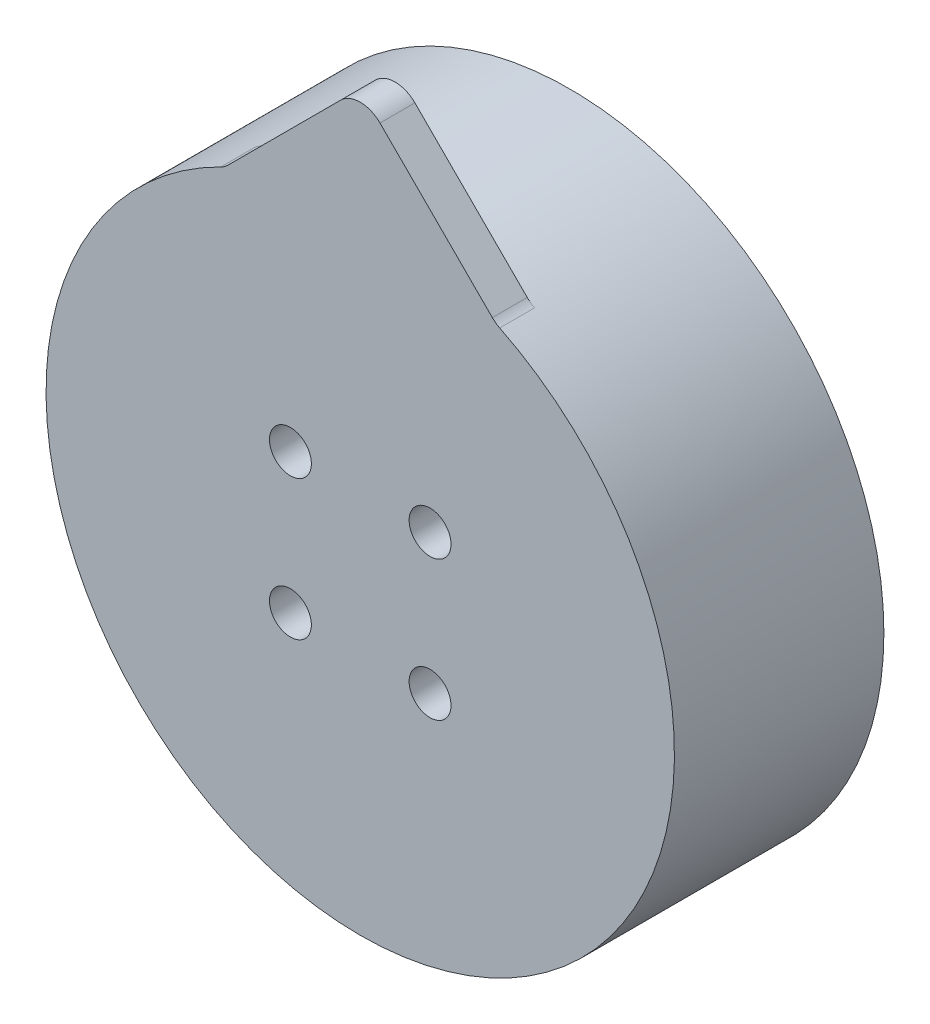
SolidWorks part; units mm, degrees
ref_plane "Front Plane" through (0, 0, 0) normal (0, 0, 1) x (1, 0, 0)
ref_plane "Top Plane" through (0, 0, 0) normal (0, 1, 0) x (1, 0, 0)
ref_plane "Right Plane" through (0, 0, 0) normal (1, 0, 0) x (0, 0, -1)
sketch "Sketch1" plane through (0, 0, 0) normal (0, 0, 1) x (1, 0, 0)
  circle A1 centre (0, 0) radius 21.844
  circle A2 centre (0, 0) radius 28.575
  dimension "D1" = 43.688
  dimension "D2" = 57.15
extrude "Boss-Extrude1" add sketch "Sketch1" along normal blind 12.7
sketch "Sketch2" plane through (0, 0, 12.7) normal (0, 0, 1) x (1, 0, 0)
  circle A1 centre (0, 0) radius 28.575
  circle A2 centre (0, 0) radius 28.575
  dimension "D1" = 0
extrude "Boss-Extrude2" add sketch "Sketch2" along normal blind 6.35
sketch "Sketch3" plane through (0, 0, 19.05) normal (0, 0, 1) x (1, 0, 0)
  line L0 (-12.3148, 25.7852) -> (0, 38.1)
  line L1 (0, 38.1) -> (12.3148, 25.7852)
  circle A0 centre (0, 0) radius 28.575 construction
  circle A2 centre (0, 0) radius 28.575
  arc A3 (12.3148, 25.7852) -> (-12.3148, 25.7852) centre (0, 0) ccw
  dimension "D1" = 38.1
  dimension "D2" = 0
extrude "Boss-Extrude3" add sketch "Sketch3" against normal blind 3.175
fillet "Fillet1" radius 2.54 3 edges at (0, 38.1, 17.4625) (12.3148, 25.7852, 17.4625) (-12.3148, 25.7852, 17.4625)
sketch "Sketch4" plane through (0, 0, 0) normal (0, 0, -1) x (-1, 0, 0)
  line L0 (0, 21.844) -> (0, -21.844) construction
  line L1 (-21.844, 0) -> (21.844, 0) construction
  line L2 (-15.446, -15.446) -> (15.446, 15.446) construction
  line L3 (-15.446, 15.446) -> (15.446, -15.446) construction
  circle A0 centre (0, 0) radius 21.844 construction
  circle A1 centre (0, 0) radius 21.844 construction
  circle A2 centre (0, 21.844) radius 1.5875
  circle A3 centre (15.446, 15.446) radius 1.5875
  circle A4 centre (21.844, 0) radius 1.5875
  circle A5 centre (15.446, -15.446) radius 1.5875
  circle A6 centre (0, -21.844) radius 1.5875
  circle A7 centre (-15.446, -15.446) radius 1.5875
  circle A8 centre (-21.844, 0) radius 1.5875
  circle A9 centre (-15.446, 15.446) radius 1.5875
  dimension "D3" = 3.175
  dimension "D1" = 90
  dimension "D2" = 45
extrude "Cut-Extrude1" cut sketch "Sketch4" against normal up to surface (12.7 mm away) up to face at (21.844, 0, 12.7)
sketch "Sketch5" plane through (0, 0, 12.7) normal (0, 0, -1) x (-1, 0, 0)
  line L1 (-6.35, -6.35) -> (6.35, -6.35) construction
  line L2 (-6.35, -6.35) -> (-6.35, 6.35) construction
  line L3 (-6.35, 6.35) -> (6.35, 6.35) construction
  line L4 (6.35, -6.35) -> (6.35, 6.35) construction
  line L5 (-6.35, -6.35) -> (6.35, 6.35) construction
  line L6 (-6.35, 6.35) -> (6.35, -6.35) construction
  circle A0 centre (-6.35, 6.35) radius 3.175
  circle A1 centre (6.35, 6.35) radius 3.175
  circle A2 centre (6.35, -6.35) radius 3.175
  circle A3 centre (-6.35, -6.35) radius 3.175
  point P0 (0, 0)
  dimension "D2" = 6.35
  dimension "D1" = 12.7
extrude "Cut-Extrude2" cut sketch "Sketch5" against normal blind 3.175
sketch "Sketch6" plane through (0, 0, 15.875) normal (0, 0, -1) x (-1, 0, 0)
  line L1 (-6.35, -6.35) -> (6.35, -6.35) construction
  line L2 (-6.35, -6.35) -> (-6.35, 6.35) construction
  line L3 (-6.35, 6.35) -> (6.35, 6.35) construction
  line L4 (6.35, -6.35) -> (6.35, 6.35) construction
  line L5 (-6.35, -6.35) -> (6.35, 6.35) construction
  line L6 (-6.35, 6.35) -> (6.35, -6.35) construction
  circle A0 centre (-6.35, 6.35) radius 1.905
  circle A1 centre (6.35, 6.35) radius 1.905
  circle A2 centre (6.35, -6.35) radius 1.905
  circle A3 centre (-6.35, -6.35) radius 1.905
  point P0 (0, 0)
  dimension "D1" = 3.81
extrude "Cut-Extrude3" cut sketch "Sketch6" against normal through all
